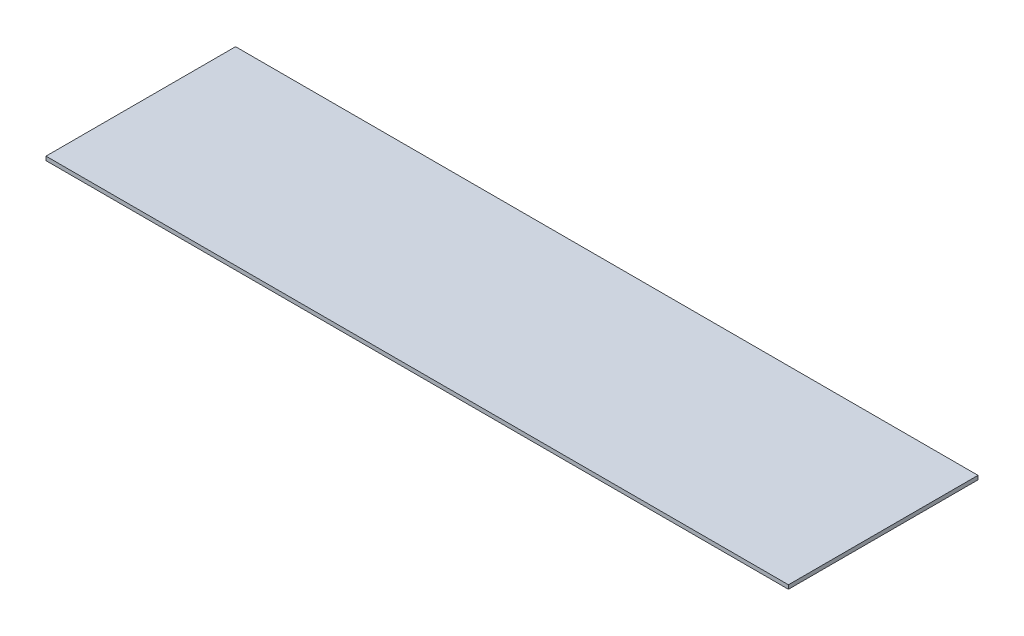
SolidWorks part; units mm, degrees
material "ABS PC"
ref_plane "Front Plane" through (0, 0, 0) normal (0, 0, 1) x (1, 0, 0)
ref_plane "Top Plane" through (0, 0, 0) normal (0, 1, 0) x (1, 0, 0)
ref_plane "Right Plane" through (0, 0, 0) normal (1, 0, 0) x (0, 0, -1)
sketch "Sketch1" plane through (0, 0, 0) normal (0, 1, 0) x (1, 0, 0)
  line L1 (0, 0) -> (596.9, 0)
  line L2 (0, 0) -> (0, 152.4)
  line L3 (0, 152.4) -> (596.9, 152.4)
  line L4 (596.9, 0) -> (596.9, 152.4)
  dimension "D1" = 596.9
  dimension "D2" = 152.4
extrude "Boss-Extrude1" add sketch "Sketch1" along normal blind 3.175
